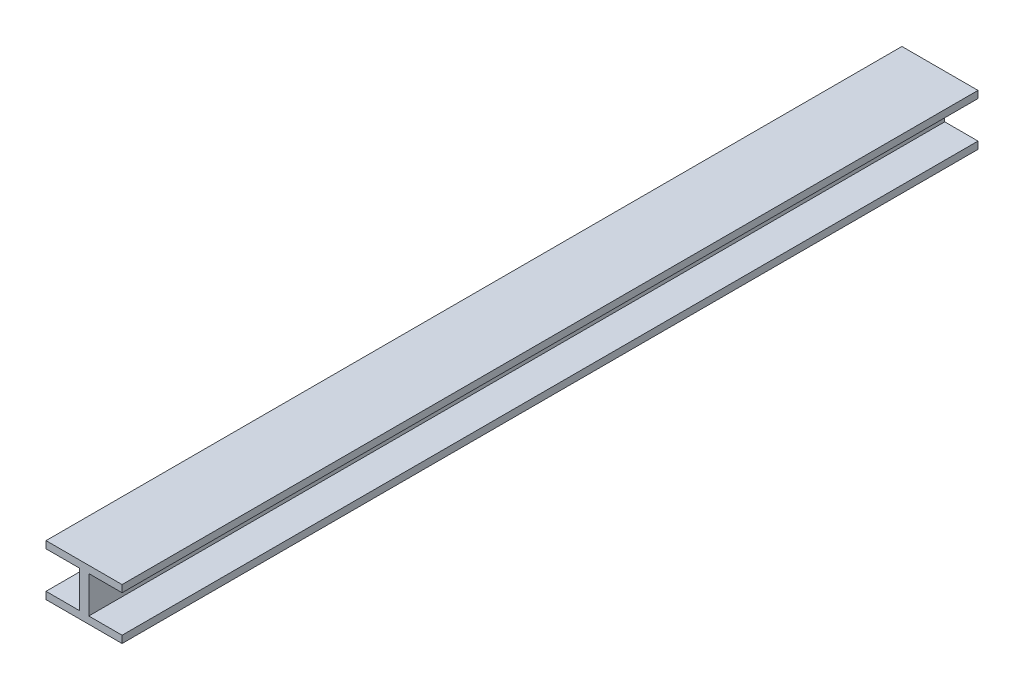
SolidWorks part; units mm, degrees
ref_plane "Front Plane" through (0, 0, 0) normal (0, 0, 1) x (1, 0, 0)
ref_plane "Top Plane" through (0, 0, 0) normal (0, 1, 0) x (1, 0, 0)
ref_plane "Right Plane" through (0, 0, 0) normal (1, 0, 0) x (0, 0, -1)
sketch "Sketch1" plane through (0, 0, 0) normal (0, 0, 1) x (1, 0, 0)
  line L0 (0, 0) -> (-17.5, 0)
  line L1 (-17.5, 0) -> (-17.5, -3.7952)
  line L2 (-17.5, -3.7952) -> (22.5, -3.7952)
  line L3 (22.5, -3.7952) -> (22.5, 0)
  line L4 (22.5, 0) -> (5, 0)
  line L5 (5, 0) -> (5, 19.3373)
  line L6 (5, 19.3373) -> (22.5, 19.3373)
  line L7 (22.5, 19.3373) -> (22.5, 23.0723)
  line L8 (22.5, 23.0723) -> (-17.5, 23.0723)
  line L9 (-17.5, 23.0723) -> (-17.5, 19.3373)
  line L10 (-17.5, 19.3373) -> (0, 19.3373)
  line L11 (0, 19.3373) -> (0, 0)
  dimension "D1" = 40
  dimension "D2" = 40
  dimension "D3" = 5
  dimension "D4" = 17.5
  dimension "D5" = 17.5
extrude "Boss-Extrude1" add sketch "Sketch1" along normal blind 450
